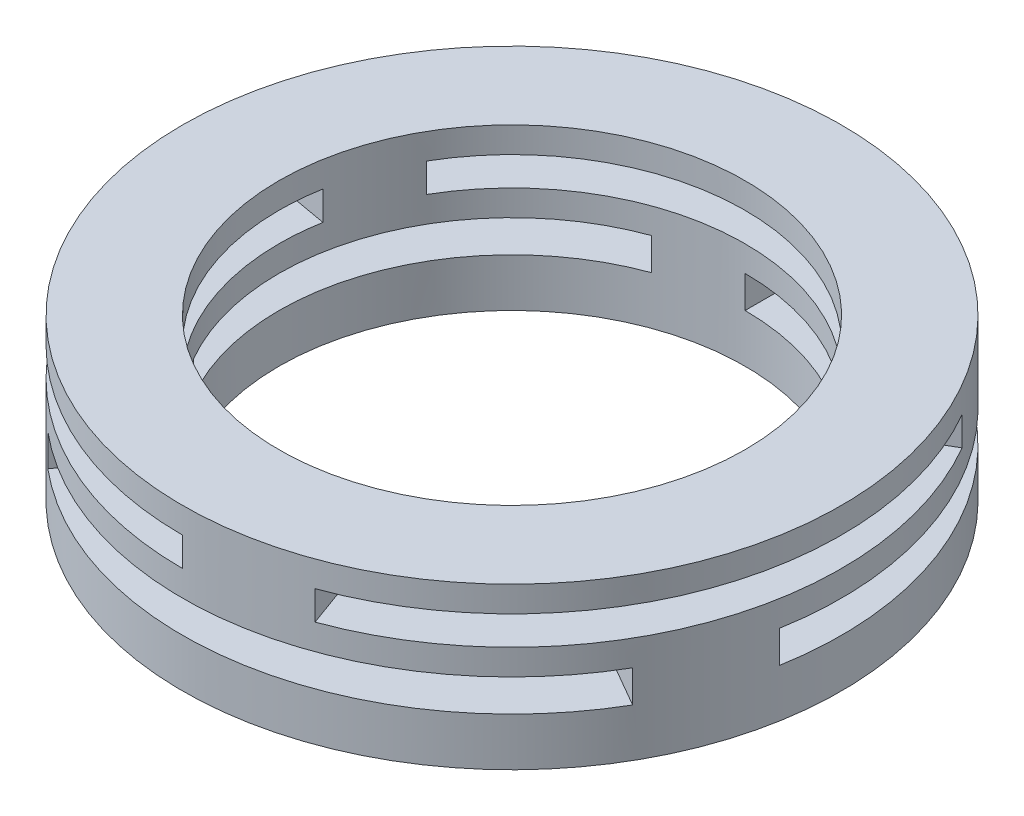
SolidWorks part; units mm, degrees
ref_plane "Plano frontal" through (0, 0, 0) normal (0, 0, 1) x (1, 0, 0)
ref_plane "Plano superior" through (0, 0, 0) normal (0, 1, 0) x (1, 0, 0)
ref_plane "Plano direito" through (0, 0, 0) normal (1, 0, 0) x (0, 0, -1)
sketch "Esboço9" plane through (0, 0, 0) normal (0, 0, 1) x (1, 0, 0)
  line L0 (0, -112.7601) -> (0, 5525.2437) construction
  line L1 (7.25, 0) -> (10.25, 0)
  line L2 (10.25, 0) -> (10.25, 5)
  line L3 (10.25, 5) -> (7.25, 5)
  line L4 (7.25, 5) -> (7.25, 0)
  dimension "D1" = 7.25
  dimension "D2" = 3
  dimension "D3" = 5
revolve "Revolução1" add sketch "Esboço9" angle 360 about L0
ref_plane "Plano4" through (0, 1.5, 0) normal (0, 1, 0) x (1, 0, 0)
sketch "Esboço12" plane through (0, 1.5, 0) normal (0, 1, 0) x (1, 0, 0)
  line L0 (0, 10.25) -> (0, 5.5)
  line L1 (5.4164, -0.9551) -> (10.0943, -1.7799)
  circle A0 centre (0, 0) radius 10.25 construction
  arc A1 (10.0943, -1.7799) -> (0, 10.25) centre (0, 0) ccw
  arc A2 (5.4164, -0.9551) -> (0, 5.5) centre (0, 0) ccw
  dimension "D1" = 100
extrude "Corte-extrusão1" cut sketch "Esboço12" along normal blind 1
pattern_circular "PadrãoCircular2" count 3 over 360 about axis through (0, 0, 0) along (0, 1, 0) of "Corte-extrusão1"
ref_plane "Plano5" through (0, 3.3, 0) normal (0, 1, 0) x (1, 0, 0)
sketch "Esboço13" plane through (0, 3.3, 0) normal (0, 1, 0) x (1, 0, 0)
  line L0 (0, 0) -> (0, 10.25) construction
  line L1 (0, 0) -> (8.8768, 5.125)
  line L2 (0, 0) -> (3.5057, -9.6318)
  arc A0 (3.5057, -9.6318) -> (8.8768, 5.125) centre (0, 0) ccw
  circle A2 centre (0, 0) radius 10.25 construction
  dimension "D1" = 60
  dimension "D2" = 100
extrude "Corte-extrusão3" cut sketch "Esboço13" along normal blind 0.9
pattern_circular "PadrãoCircular4" count 3 over 360 about axis through (0, 0, 0) along (0, 1, 0) of "Corte-extrusão3"
